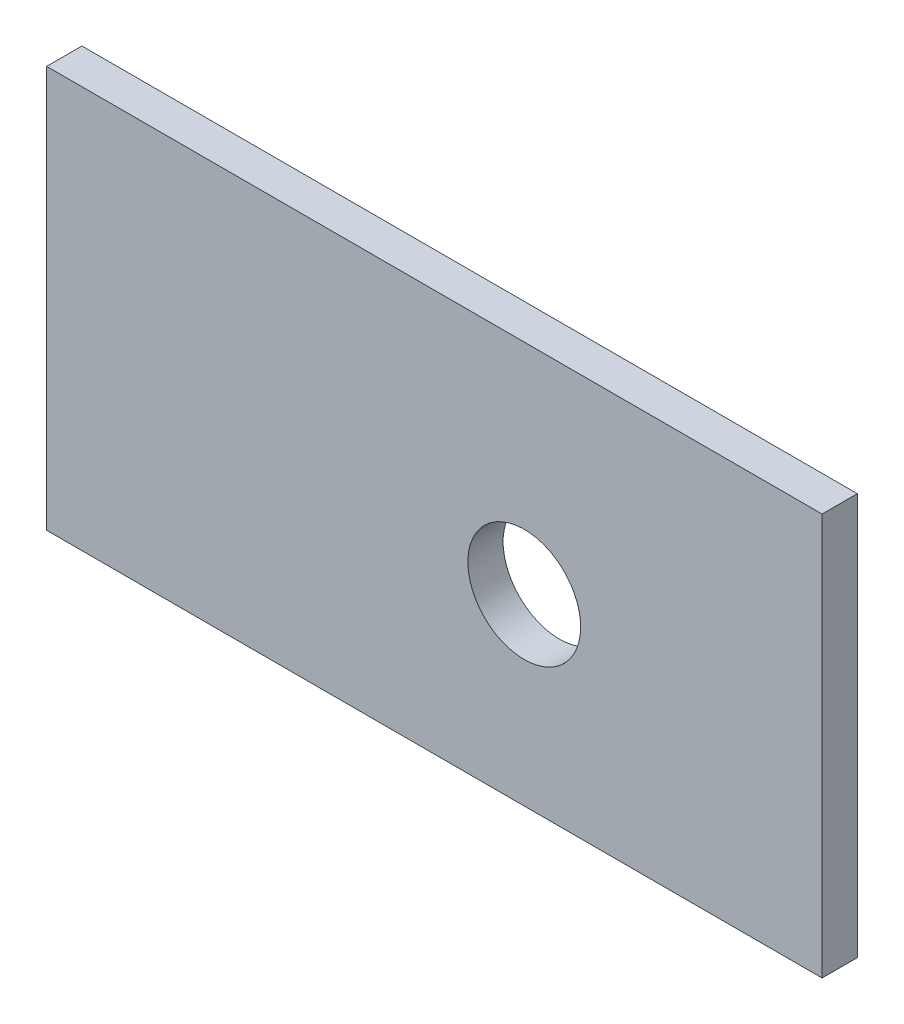
SolidWorks part; units mm, degrees
ref_plane "정면" through (0, 0, 0) normal (0, 0, 1) x (1, 0, 0)
ref_plane "윗면" through (0, 0, 0) normal (0, 1, 0) x (1, 0, 0)
ref_plane "우측면" through (0, 0, 0) normal (1, 0, 0) x (0, 0, -1)
sketch "스케치2" plane through (0, 0, 0) normal (0, 0, 1) x (1, 0, 0)
  line L1 (-55, -28.5) -> (55, -28.5)
  line L2 (-55, -28.5) -> (-55, 28.5)
  line L3 (-55, 28.5) -> (55, 28.5)
  line L4 (55, -28.5) -> (55, 28.5)
  line L5 (-55, -28.5) -> (55, 28.5) construction
  line L6 (-55, 28.5) -> (55, -28.5) construction
  circle A0 centre (12.75, -2.5) radius 8
  point P0 (0, 0)
  dimension "D5" = 16
  dimension "D1" = 57
  dimension "D2" = 110
  dimension "D3" = 67.75
  dimension "D4" = 31
extrude "보스-돌출1" add sketch "스케치2" along normal blind 5
